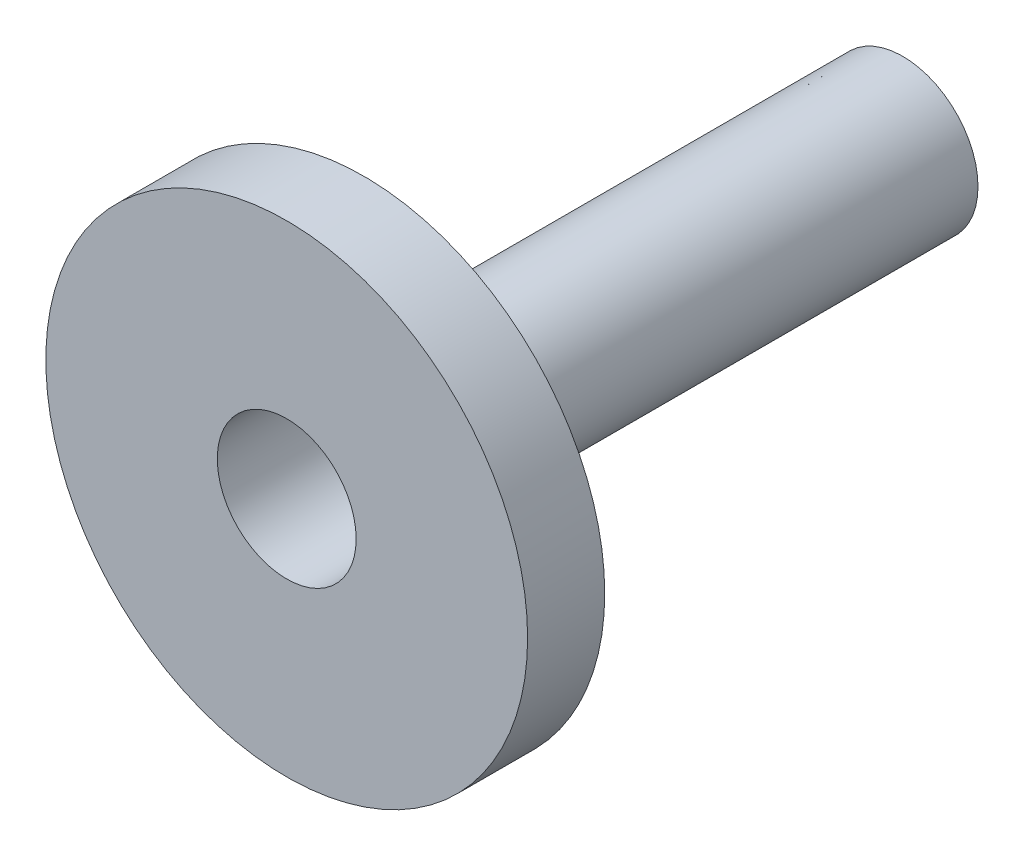
SolidWorks part; units mm, degrees
ref_plane "Front Plane" through (0, 0, 0) normal (0, 0, 1) x (1, 0, 0)
ref_plane "Top Plane" through (0, 0, 0) normal (0, 1, 0) x (1, 0, 0)
ref_plane "Right Plane" through (0, 0, 0) normal (1, 0, 0) x (0, 0, -1)
sketch "Sketch1" plane through (0, 0, 0) normal (0, 0, 1) x (1, 0, 0)
  circle A0 centre (0, 0) radius 18
  circle A1 centre (0, 0) radius 19.5
  dimension "D1" = 1.5
extrude "Extrude1" add sketch "Sketch1" against normal blind 139.7
sketch "Sketch2" plane through (0, 0, 0) normal (0, 0, 1) x (1, 0, 0)
  circle A0 centre (0, 0) radius 18
  circle A1 centre (0, 0) radius 62.4463
  circle A2 centre (0, 0) radius 18 construction
extrude "Extrude2" add sketch "Sketch2" along normal blind 19.9898
sketch "Sketch3" plane through (0, 0, 0) normal (1, 0, 0) x (0, 0, -1)
  line L0 (143.1001, 0) -> (104.6433, 0) construction
  line L1 (139.7, 18) -> (139.7, 14.5)
  line L2 (139.7, -18) -> (139.7, 18) construction
  line L3 (139.7, -19.5) -> (139.7, 19.5) construction
  line L4 (139.7, 14.5) -> (136.2, 18)
  line L5 (136.2, 18) -> (139.7, 18)
  dimension "D1" = 3.5
  dimension "D2" = 3.5
revolve "Revolve1" add sketch "Sketch3" angle 360 about L0
